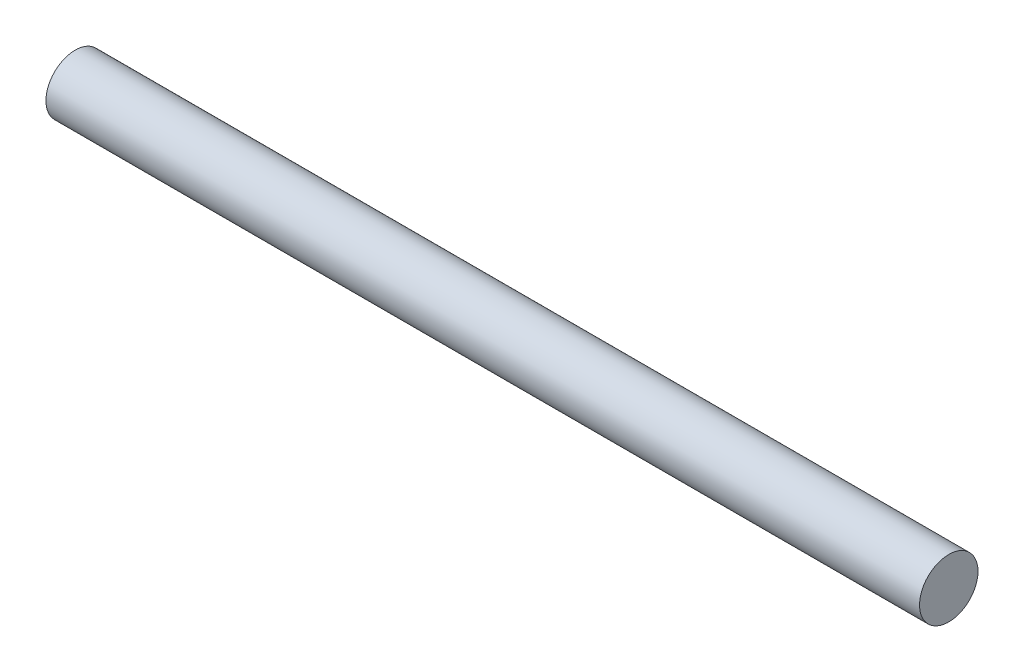
SolidWorks part; units mm, degrees
ref_plane "Front Plane" through (0, 0, 0) normal (0, 0, 1) x (1, 0, 0)
ref_plane "Top Plane" through (0, 0, 0) normal (0, 1, 0) x (1, 0, 0)
ref_plane "Right Plane" through (0, 0, 0) normal (1, 0, 0) x (0, 0, -1)
sketch "Sketch1" plane through (0, 0, 0) normal (1, 0, 0) x (0, 0, -1)
  circle A0 centre (0, 0) radius 8.5
  dimension "D1" = 17
extrude "Boss-Extrude1" add sketch "Sketch1" along normal blind 254
